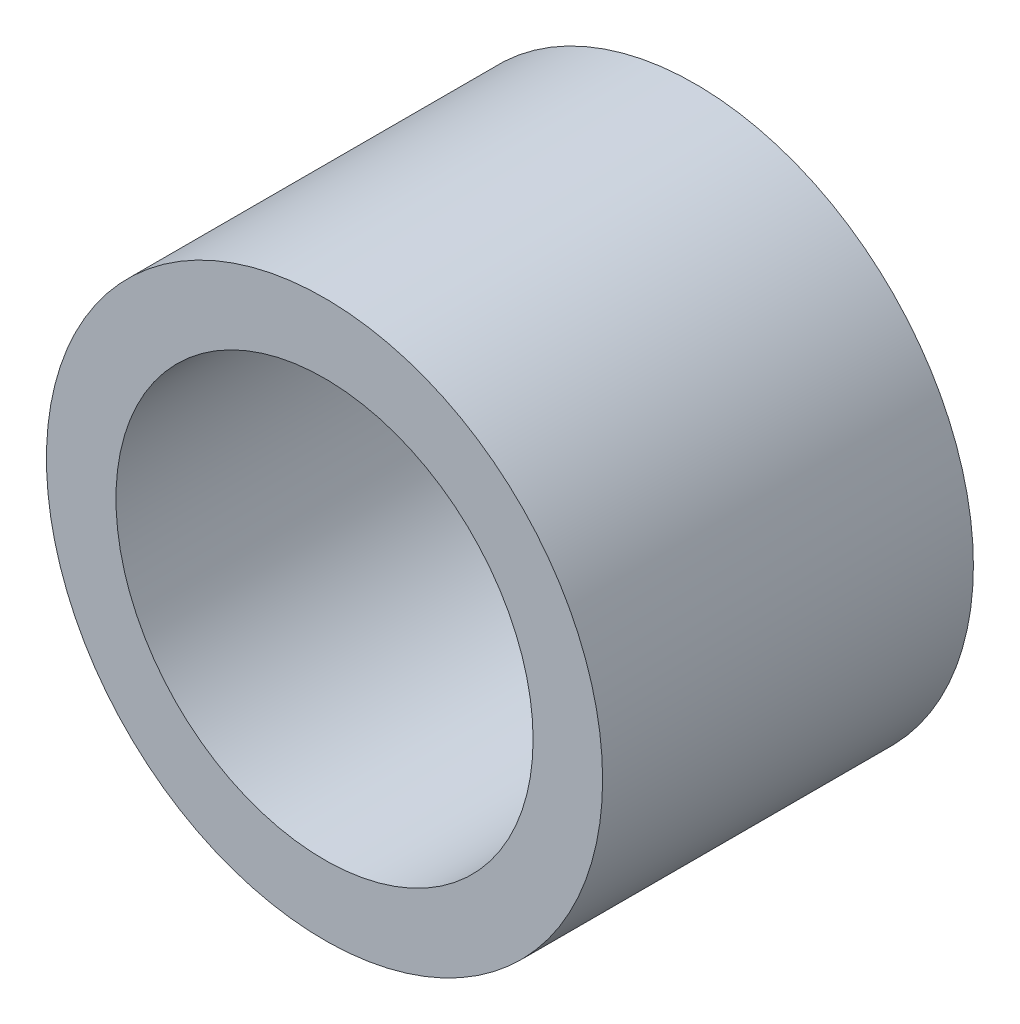
SolidWorks part; units mm, degrees
ref_plane "Plan de face" through (0, 0, 0) normal (0, 0, 1) x (1, 0, 0)
ref_plane "Plan de dessus" through (0, 0, 0) normal (0, 1, 0) x (1, 0, 0)
ref_plane "Plan de droite" through (0, 0, 0) normal (1, 0, 0) x (0, 0, -1)
sketch "Esquisse1" plane through (0, 0, 0) normal (0, 0, 1) x (1, 0, 0)
  circle A0 centre (0, 0) radius 4.5
  circle A1 centre (0, 0) radius 6
  dimension "D1" = 9
  dimension "D2" = 12
extrude "Boss.-Extru.1" add sketch "Esquisse1" along normal mid plane 8
